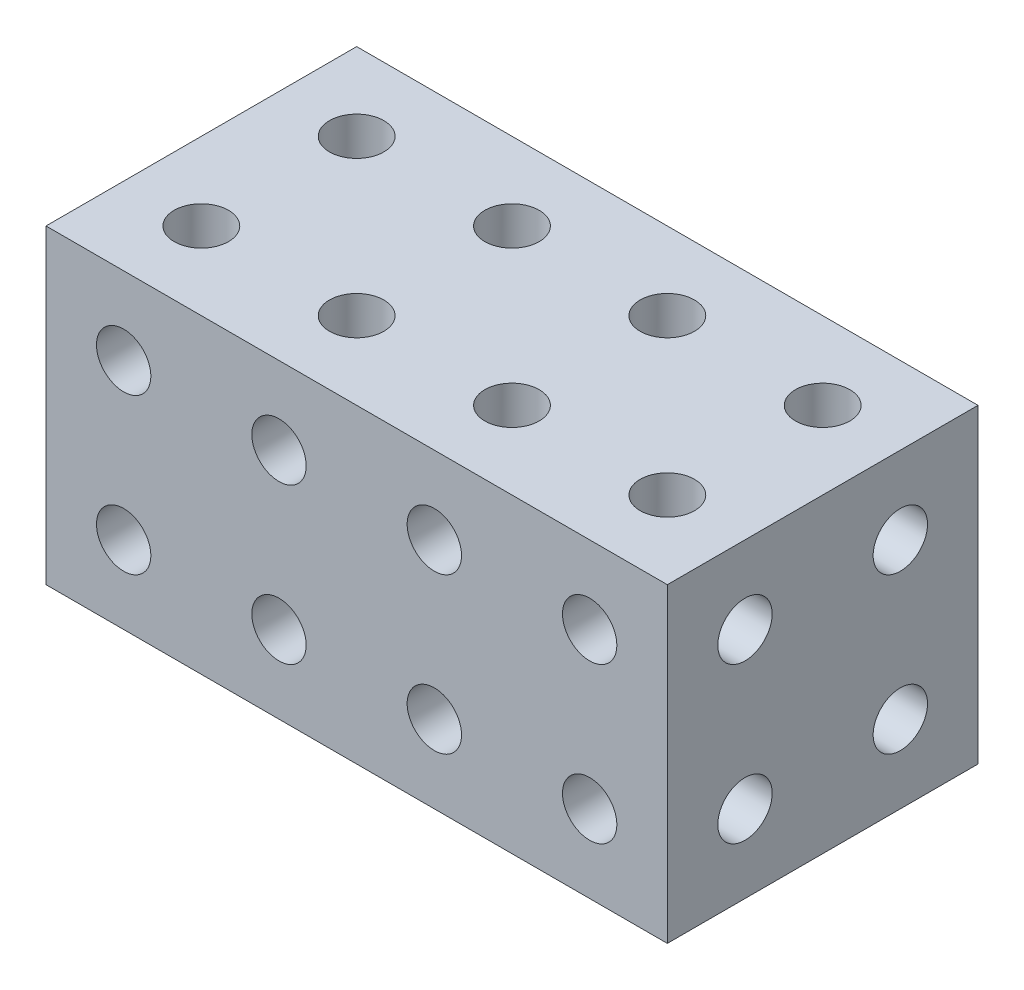
SolidWorks part; units mm, degrees
ref_plane "Plan de face" through (0, 0, 0) normal (0, 0, 1) x (1, 0, 0)
ref_plane "Plan de dessus" through (0, 0, 0) normal (0, 1, 0) x (1, 0, 0)
ref_plane "Plan de droite" through (0, 0, 0) normal (1, 0, 0) x (0, 0, -1)
sketch "Esquisse1" plane through (0, 0, 0) normal (1, 0, 0) x (0, 0, -1)
  line L1 (0, 0) -> (20, 0)
  line L2 (0, 0) -> (0, 20)
  line L3 (0, 20) -> (20, 20)
  line L4 (20, 0) -> (20, 20)
  dimension "D1" = 20
  dimension "D2" = 20
extrude "Boss.-Extru.1" add sketch "Esquisse1" along normal blind 40
sketch "Esquisse2" plane through (0, 20, 0) normal (0, 1, 0) x (1, 0, 0)
  line L0 (0, 15) -> (40, 15) construction
  line L4 (40, 20) -> (0, 20) construction
  circle A0 centre (5, 15) radius 1.75
  circle A1 centre (15, 15) radius 1.75
  circle A2 centre (25, 15) radius 1.75
  circle A3 centre (35, 15) radius 1.75
  circle A4 centre (5, 5) radius 1.75
  circle A5 centre (15, 5) radius 1.75
  circle A6 centre (25, 5) radius 1.75
  circle A7 centre (35, 5) radius 1.75
  circle A8 centre (5, -5) radius 1.75
  circle A9 centre (15, -5) radius 1.75
  circle A10 centre (25, -5) radius 1.75
  circle A11 centre (35, -5) radius 1.75
  circle A12 centre (5, -15) radius 1.75
  circle A13 centre (15, -15) radius 1.75
  circle A14 centre (25, -15) radius 1.75
  circle A15 centre (35, -15) radius 1.75
  dimension "D4" = 3.5
  dimension "D1" = 5
  dimension "D2" = 10
  dimension "D3" = 10
  dimension "D5" = 10
  dimension "D6" = 5
  dimension "D7" = 4
extrude "Enlèv. mat.-Extru.1" cut sketch "Esquisse2" against normal through all
sketch "Esquisse3" plane through (0, 0, 0) normal (0, 0, 1) x (1, 0, 0)
  line L0 (0, 15) -> (40, 15) construction
  line L1 (0, 20) -> (0, 0) construction
  line L3 (40, 20) -> (0, 20) construction
  circle A0 centre (5, 15) radius 1.75
  circle A1 centre (15, 15) radius 1.75
  circle A2 centre (25, 15) radius 1.75
  circle A3 centre (35, 15) radius 1.75
  circle A4 centre (5, 5) radius 1.75
  circle A5 centre (15, 5) radius 1.75
  circle A6 centre (25, 5) radius 1.75
  circle A7 centre (35, 5) radius 1.75
  dimension "D4" = 3.5
  dimension "D1" = 5
  dimension "D2" = 10
  dimension "D3" = 10
  dimension "D5" = 10
  dimension "D6" = 5
  dimension "D7" = 2
extrude "Enlèv. mat.-Extru.2" cut sketch "Esquisse3" against normal blind 40
sketch "Esquisse4" plane through (40, 0, 0) normal (1, 0, 0) x (0, 0, -1)
  line L0 (0, 15) -> (20, 15) construction
  line L1 (0, 20) -> (0, 0) construction
  line L3 (20, 20) -> (0, 20) construction
  circle A0 centre (5, 15) radius 1.75
  circle A1 centre (15, 15) radius 1.75
  circle A2 centre (25, 15) radius 1.75
  circle A3 centre (35, 15) radius 1.75
  circle A4 centre (5, 5) radius 1.75
  circle A5 centre (15, 5) radius 1.75
  dimension "D1" = 3.5
  dimension "D2" = 5
  dimension "D4" = 5
  dimension "D3" = 4
  dimension "D5" = 2
extrude "Enlèv. mat.-Extru.3" cut sketch "Esquisse4" against normal blind 40
